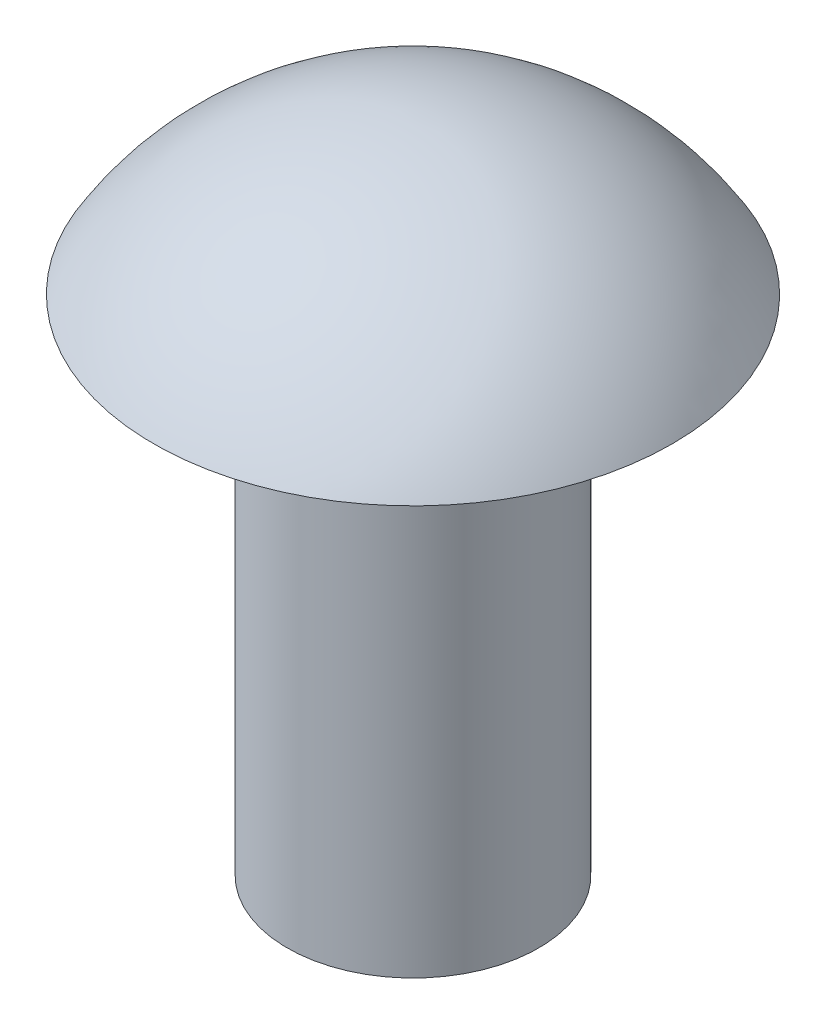
SolidWorks part; units mm, degrees
material "AISI 1010, rullato a caldo"
ref_plane "Piano frontale" through (0, 0, 0) normal (0, 0, 1) x (1, 0, 0)
ref_plane "Piano superiore" through (0, 0, 0) normal (0, 1, 0) x (1, 0, 0)
ref_plane "Piano destro" through (0, 0, 0) normal (1, 0, 0) x (0, 0, -1)
sketch "Schizzo1" plane through (0, 0, 0) normal (0, 0, 1) x (1, 0, 0)
  line L0 (0, 30.7896) -> (0, -44.6372) construction
  line L1 (0, -6.9238) -> (2.5, -6.9238)
  line L2 (2.5, -6.9238) -> (2.5, 3.0762)
  line L3 (2.5, 3.0762) -> (5.1514, 3.0762)
  line L4 (0, -6.9238) -> (0, 6)
  arc A0 (5.1514, 3.0762) -> (0, 6) centre (0, 0) ccw
  dimension "D3" = 6
  dimension "D1" = 10
  dimension "D2" = 2.5
revolve "Rivoluzione1" add sketch "Schizzo1" angle 360 about L0
